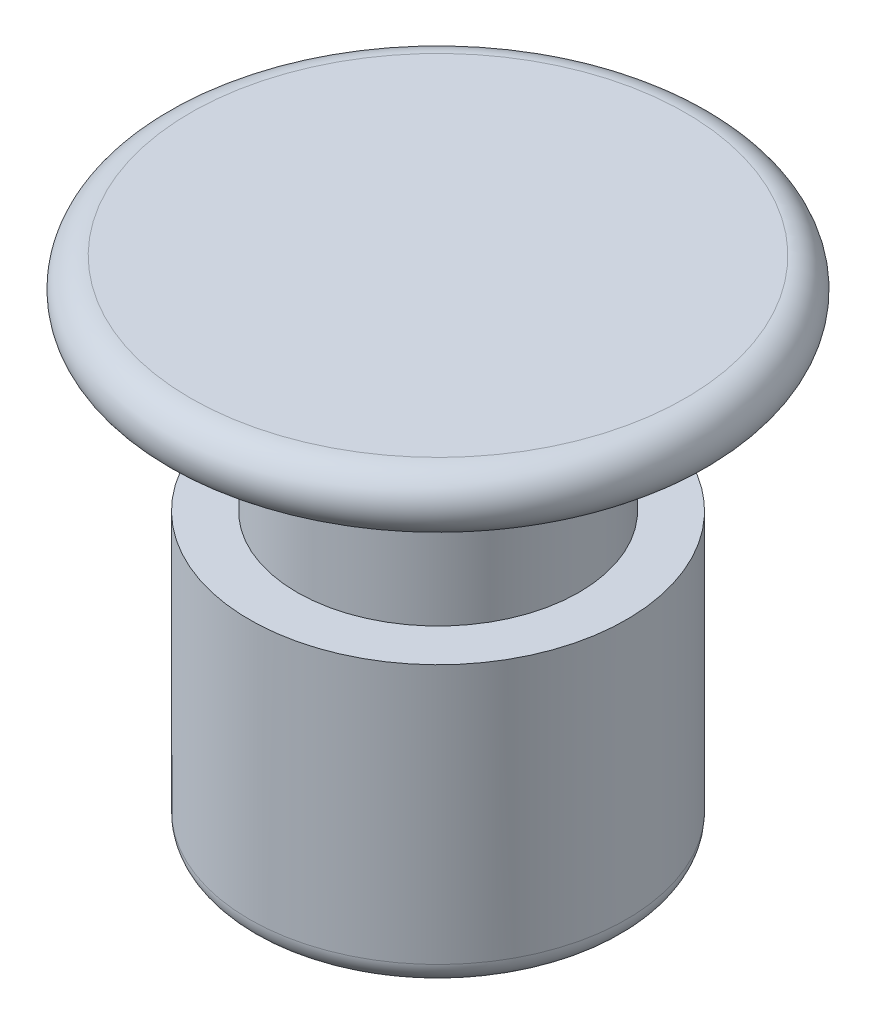
SolidWorks part; units mm, degrees
material "Plain Carbon Steel"
ref_plane "Front Plane" through (0, 0, 0) normal (0, 0, 1) x (1, 0, 0)
ref_plane "Top Plane" through (0, 0, 0) normal (0, 1, 0) x (1, 0, 0)
ref_plane "Right Plane" through (0, 0, 0) normal (1, 0, 0) x (0, 0, -1)
sketch "Sketch2" plane through (0, 0, 0) normal (0, 0, 1) x (1, 0, 0)
  line L0 (0, 94.6089) -> (0, -124.2387) construction
  line L1 (-109.7248, 0) -> (112.8211, 0) construction
  line L4 (1.5875, -1.397) -> (1.5875, -10.0584)
  line L5 (1.5875, -10.0584) -> (0, -10.0584)
  line L6 (0, -10.0584) -> (0, 0)
  line L7 (0, 0) -> (2.7837, 0)
  line L8 (1.5875, -1.397) -> (2.9476, -0.6118)
  line L9 (3.1115, 3.28) -> (3.1115, -4.1331) construction
  line L10 (1.5875, -1.397) -> (12.4953, 4.9006) construction
  arc A0 (2.7837, 0) -> (2.9476, -0.6118) centre (2.7837, -0.3278) cw
  point P12 (4.0072, 0)
  dimension "D1" = 3.1115
  dimension "D2" = 60
  dimension "D3" = 1.5875
  dimension "D4" = 8.6614
  dimension "D5" = 1.397
revolve "Revolve1" add sketch "Sketch2" angle 360 about L0
sketch "Sketch3" plane through (0, -10.0584, 0) normal (0, -1, 0) x (1, 0, 0)
  circle A0 centre (0, 0) radius 2.1209
  dimension "D1" = 4.2418
extrude "Boss-Extrude1" add sketch "Sketch3" against normal blind 7.5692
sketch "Sketch5" plane through (0, -2.4892, 0) normal (0, 1, 0) x (1, 0, 0)
  circle A0 centre (0, 0) radius 2.1209
  circle A1 centre (0, 0) radius 2.1209 construction
extrude "Cut-Extrude1" cut sketch "Sketch5" against normal blind 8.636 from offset 3.175 offset against normal yes
fillet "Fillet1" radius 0.254 1 edges at (0, -5.6642, 2.1209)
